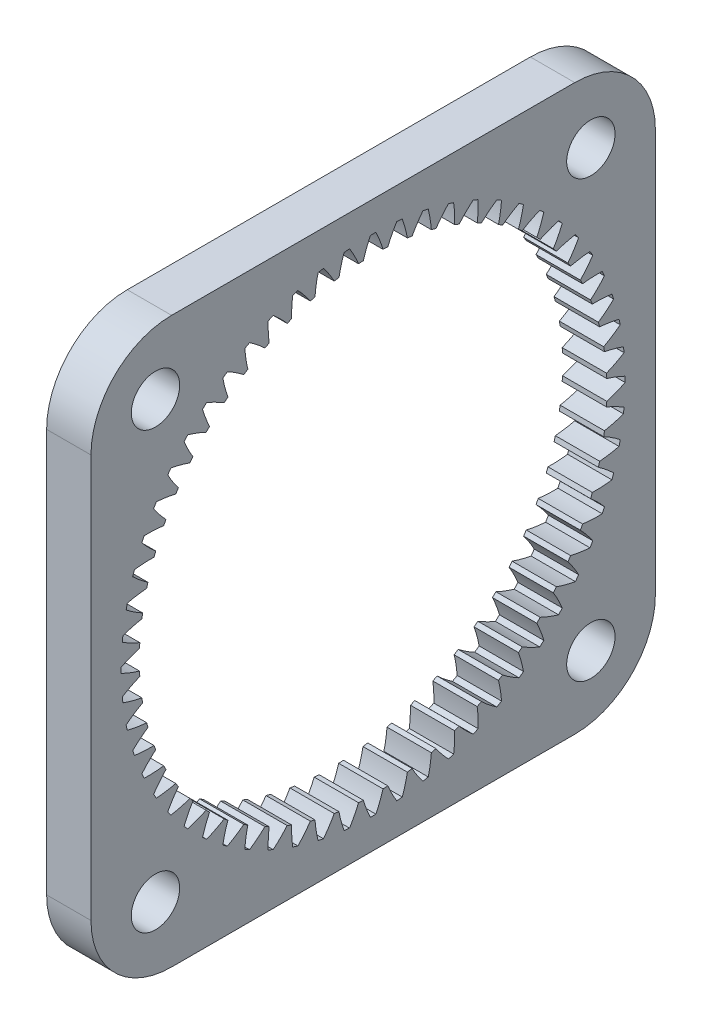
SolidWorks part; units mm, degrees
ref_plane "Plane1" through (0, 0, 0) normal (0, 0, 1) x (1, 0, 0)
ref_plane "Plane2" through (0, 0, 0) normal (0, 1, 0) x (1, 0, 0)
ref_plane "Plane3" through (0, 0, 0) normal (1, 0, 0) x (0, 0, -1)
sketch "HoldingSke" plane through (0, 0, 0) normal (0, 1, 0) x (1, 0, 0)
  line L0 (0, 0) -> (0.5, -0.866)
  line L1 (-15, 0) -> (100, 0) construction
  line L2 (0, 0) -> (-2.1039, 2.3779)
  line L3 (0, 0) -> (-11.863, 4.5341)
  line L4 (0, 0) -> (4.318, 7.479)
  line L5 (0, 0) -> (-23.7986, -8.8762)
  line L6 (0, 0) -> (-10.5278, -7.1032)
  line L7 (-2.1039, 2.3779) -> (3.3635, 27.1825)
  line L8 (-76.2, 3.3779) -> (-54.61, 3.3779)
  line L9 (-71.009, 38.7566) -> (-53.1078, 45.2721)
  line L10 (-76.2, 71.12) -> (104.1128, 71.12)
  line L11 (0, 0) -> (-5.5, 0)
  line L12 (-76.2, 101.6) -> (-76.162, 101.6)
  line L13 (24.9733, 27.94) -> (52.9518, 28.4284)
  line L14 (24.9733, 27.94) -> (24.9743, 27.94)
  line L15 (24.9733, 27.94) -> (100.4006, 29.5858)
  circle A0 centre (0, 0) radius 35
  circle A1 centre (0, 0) radius 12.7
  circle A2 centre (0, 0) radius 12.7
  dimension "MHD" = 25.4
  dimension "Hub_dia" = 25.4
  dimension "Diameter" = 70
  dimension "Num_teeth" = 60
  dimension "Pitch" = 1
  dimension "Overall_len" = 25.4
  dimension "Show_teeth" = 60
  dimension "Thickness" = 12.7
  dimension "OAL" = 25.4001
  dimension "T_dim" = 21.59
  dimension "Ap" = 20
  dimension "H" = 19.05
  dimension "Pitch_radius" = 180.3128
  dimension "Width" = 5.5
  dimension "Backlash" = 0.038
  dimension "Addendum_fac" = 1
  dimension "Dedendum_fac" = 1.25
  dimension "Clearance_fac" = 0.25
  dimension "Dedendum_add" = 0.001
  dimension "Module" = 1
sketch "BasProSke" plane through (0, 0, 0) normal (0, 1, 0) x (1, 0, 0)
  line L0 (-10, 0) -> (60, 0) construction
  line L1 (0, 29) -> (0, 35)
  line L2 (0, 29) -> (5.5, 29)
  line L3 (5.5, 29) -> (5.5, 35)
  line L4 (5.5, 35) -> (0, 35)
  dimension "Diameter" = 70
  dimension "Thickness" = 5.5
  dimension "Inside_diameter" = 58
revolve "Base-Revolve" add sketch "BasProSke" angle 360 about L0
sketch "TooCutSke" plane through (0, 0, 0) normal (1, 0, 0) x (0, 0, -1)
  line L3 (0.8803, 29.9871) -> (0.8803, 53.6633) construction
  line L4 (0, 0) -> (0, 59.563) construction
  line L5 (0, 0) -> (-3.576, 68.2339) construction
  line L6 (-13.1633, 24.7167) -> (36.4631, 27.3175) construction
  circle A0 centre (0, 0) radius 30 construction
  circle A1 centre (0, 0) radius 31.251 construction
  circle A2 centre (0, 0) radius 25.3717 construction
  circle A3 centre (0, 0) radius 28.9746 construction
  arc A4 (1.2274, 28.9486) -> (0.3395, 31.2492) centre (-13.1633, 24.7167) ccw
  arc A5 (1.2274, 28.9486) -> (-1.2274, 28.9486) centre (0, 0) ccw
  arc A6 (0.3395, 31.2492) -> (-0.3395, 31.2492) centre (0, 0) ccw
  arc A7 (-0.3395, 31.2492) -> (-1.2274, 28.9486) centre (13.1633, 24.7167) ccw
  dimension "Pitch_dia" = 60
  dimension "Base_dia" = 50.7434
  dimension "Root_dia" = 62.502
  dimension "Overcut_dia" = 57.9492
  dimension "Flank_rad" = 15
  dimension "Half_ang" = 3
  dimension "Half_CT" = 0.8803
extrude "ToothCut" cut sketch "TooCutSke" along normal through all
fillet "Breaks" [suppressed] radius 0.1
fillet "RootFillets" [suppressed] radius 0.251
pattern_circular "TeethCuts" count 60 every 6 about axis through (-10, 0, 0) along (1, 0, 0) of "RootFillets", "Breaks", "ToothCut"
sketch "Croquis1" plane through (5.5, 0, 0) normal (1, 0, 0) x (0, 0, -1)
  line L1 (-35, 35) -> (35, 35)
  line L2 (-35, 35) -> (-35, -35)
  line L3 (-35, -35) -> (35, -35)
  line L4 (35, 35) -> (35, -35)
  line L5 (-35, 35) -> (35, -35) construction
  line L6 (-35, -35) -> (35, 35) construction
  circle A0 centre (0, 0) radius 35
  dimension "D1" = 70
  dimension "D2" = 70
extrude "Saliente-Extruir1" add sketch "Croquis1" against normal through all contours A0 L1 L2 | A0 L4 L1 | A0 L3 L4 | A0 L2 L3
fillet "Redondeo1" radius 10 4 edges at (2.75, 35, 35) (2.75, -35, 35) (2.75, -35, -35) (2.75, 35, -35)
sketch "Croquis3" plane through (5.5, 0, 0) normal (1, 0, 0) x (0, 0, -1)
  line L0 (-25, 35) -> (25, 35) construction
  line L1 (-35, 25) -> (-35, -25) construction
  line L2 (35, 25) -> (35, -25) construction
  line L3 (-25, -35) -> (25, -35) construction
  circle A0 centre (-27, 27) radius 3
  circle A1 centre (27, 27) radius 3
  circle A2 centre (-27, -27) radius 3
  circle A3 centre (27, -27) radius 3
  dimension "D1" = 6
  dimension "D2" = 6
  dimension "D3" = 6
  dimension "D4" = 6
  dimension "D5" = 8
  dimension "D6" = 8
  dimension "D7" = 8
  dimension "D8" = 8
  dimension "D9" = 8
  dimension "D10" = 8
  dimension "D11" = 8
  dimension "D12" = 8
extrude "Cortar-Extruir1" cut sketch "Croquis3" against normal blind 6 contours A1 | A2 | A0 | A3
equation "' \"Module@HoldingSke\" = 6.35"
equation "' \"Num_teeth@HoldingSke\" = 24"
equation "' \"Ap@HoldingSke\" =  14.5"
equation "' \"Ap@HoldingSke\" = 14.5"
equation "' \"Width@HoldingSke\" = 12"
equation "' \"Diameter@HoldingSke\" = 8 * 25.4"
equation "' \"Show_teeth@HoldingSke\" = 100"
equation "' \"Backlash@HoldingSke\" = 0.009 * 25.4"
equation "' \"Addendum_fac@HoldingSke\" = 1.0"
equation "' \"Dedendum_fac@HoldingSke\" = 1.25"
equation "' \"Dedendum_add@HoldingSke\" = 0.00005 * 25.4"
equation "' \"Clearance_fac@HoldingSke\" = 0.25"
equation "\"Pitch@HoldingSke\" = 1 / \"Module@HoldingSke\" "
equation "\"Overcut_dia@TooCutSke\" = (\"Num_teeth@HoldingSke\" - 2 * \"Addendum_fac@HoldingSke\") / \"Pitch@HoldingSke\" - 0.002 * 25.4"
equation "\"Pitch_dia@TooCutSke\" = \"Num_teeth@HoldingSke\" / \"Pitch@HoldingSke\""
equation "\"Base_dia@TooCutSke\" = \"Num_teeth@HoldingSke\" / \"Pitch@HoldingSke\" * cos((\"Ap@HoldingSke\"  * 3.14159265 / 180)) * 0.90"
equation "\"Root_dia@TooCutSke\" = \"Num_teeth@HoldingSke\"  / \"Pitch@HoldingSke\" + 2 *  \"Dedendum_fac@HoldingSke\"/ \"Pitch@HoldingSke\" + \"Dedendum_add@HoldingSke\" * 2"
equation "\"Half_ang@TooCutSke\" = 180 / \"Num_teeth@HoldingSke\""
equation "\"Half_CT@TooCutSke\" = \"Num_teeth@HoldingSke\" / \"Pitch@HoldingSke\" * sin((3.14159265 / 2 / \"Num_teeth@HoldingSke\")) / 2 + 10 * \"Backlash@HoldingSke\" / 4"
equation "\"Flank_rad@TooCutSke\" = \"Num_teeth@HoldingSke\" / \"Pitch@HoldingSke\" / 4"
equation "\"Radius@RootFillets\"= \"Clearance_fac@HoldingSke\" / \"Pitch@HoldingSke\" + \"Dedendum_add@HoldingSke\""
equation "\"Break_rad@Breaks\" = 0.02 / \"Pitch@HoldingSke\" * 5"
equation "\"Num_teeth@TeethCuts\" = int( \"Show_teeth@HoldingSke\" ) + 1"
equation "\"Num_teeth@TeethCuts\" = ((sgn( \"Num_teeth@TeethCuts\" - \"Num_teeth@HoldingSke\" )-1)*( \"Num_teeth@TeethCuts\" - \"Num_teeth@HoldingSke\" ))/-2+ \"Num_teeth@HoldingSke\""
equation "\"Num_teeth@TeethCuts\" = ((sgn( \"Num_teeth@TeethCuts\" - 2.0)+1)*( \"Num_teeth@TeethCuts\" - 2.0))/2 +2.0"
equation "\"Angle@TeethCuts\" = 360.0 / \"Num_teeth@HoldingSke\""
equation "\"Diameter@BasProSke\" = \"Num_teeth@HoldingSke\"  / \"Pitch@HoldingSke\" + 2 *  \"Dedendum_fac@HoldingSke\"/ \"Pitch@HoldingSke\" + \"Dedendum_add@HoldingSke\" * 2 + 0.002 * 25.4"
equation "\"Diameter@BasProSke\" = ((sgn( \"Diameter@BasProSke\"  - \"Diameter@HoldingSke\" )+1)*( \"Diameter@BasProSke\"  - \"Diameter@HoldingSke\" ))/2 + \"Diameter@HoldingSke\""
equation "\"Inside_diameter@BasProSke\" =  (\"Num_teeth@HoldingSke\" - 2 * \"Addendum_fac@HoldingSke\") / \"Pitch@HoldingSke\" "
equation "\"Thickness@BasProSke\"  = \"Width@HoldingSke\""
